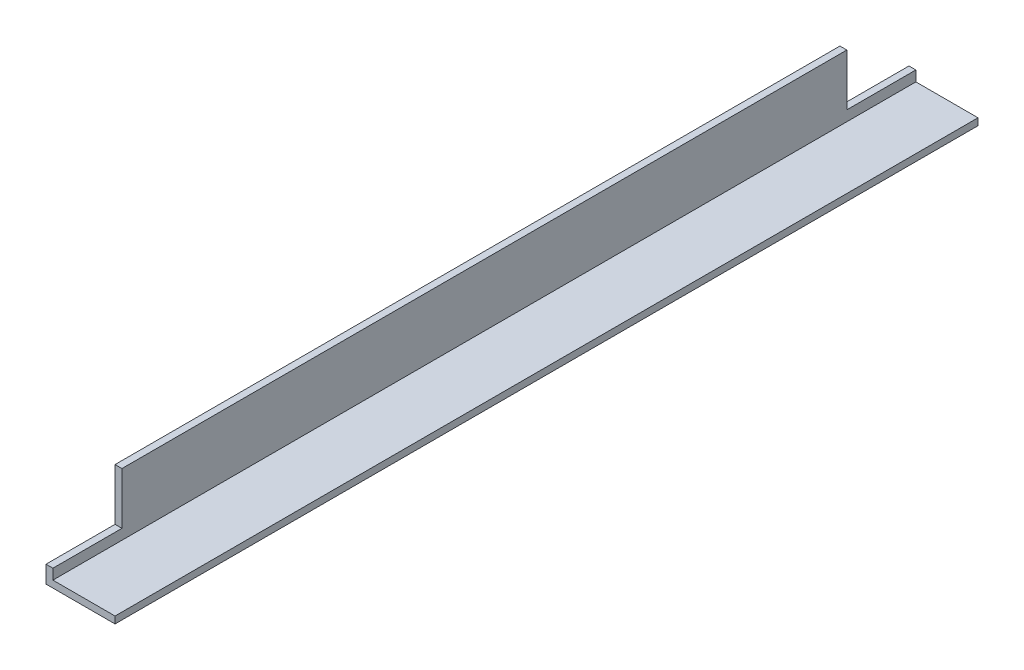
SolidWorks part; units mm, degrees
ref_plane "Спереди" through (0, 0, 0) normal (0, 0, 1) x (1, 0, 0)
ref_plane "Сверху" through (0, 0, 0) normal (0, 1, 0) x (1, 0, 0)
ref_plane "Справа" through (0, 0, 0) normal (1, 0, 0) x (0, 0, -1)
sketch "Эскиз1" plane through (0, 0, 0) normal (0, 0, 1) x (1, 0, 0)
  line L0 (0, 0) -> (0, 40)
  line L1 (0, 40) -> (4, 40)
  line L2 (4, 40) -> (4, 4)
  line L3 (4, 4) -> (40, 4)
  line L4 (40, 4) -> (40, 0)
  line L5 (40, 0) -> (0, 0)
  dimension "D1" = 40
  dimension "D2" = 40
  dimension "D3" = 4
  dimension "D4" = 4
extrude "Бобышка-Вытянуть1" add sketch "Эскиз1" along normal blind 500
sketch "Эскиз2" plane through (0, 0, 0) normal (-1, 0, 0) x (0, 0, 1)
  line L0 (0, 10) -> (40, 10)
  line L1 (0, 40) -> (0, 0) construction
  line L2 (40, 10) -> (40, 40)
  line L3 (500, 40) -> (0, 40) construction
  line L4 (40, 40) -> (0, 40)
  line L5 (0, 40) -> (0, 10)
  dimension "D1" = 30
  dimension "D2" = 40
extrude "Вырез-Вытянуть1" cut sketch "Эскиз2" against normal through all
sketch "Эскиз3" plane through (0, 0, 0) normal (-1, 0, 0) x (0, 0, 1)
  line L0 (500, 10) -> (460, 10)
  line L1 (500, 40) -> (500, 0) construction
  line L2 (460, 10) -> (460, 40)
  line L3 (460, 40) -> (500, 40)
  line L4 (500, 40) -> (500, 10)
  dimension "D1" = 30
  dimension "D2" = 40
extrude "Вырез-Вытянуть2" cut sketch "Эскиз3" against normal through all
